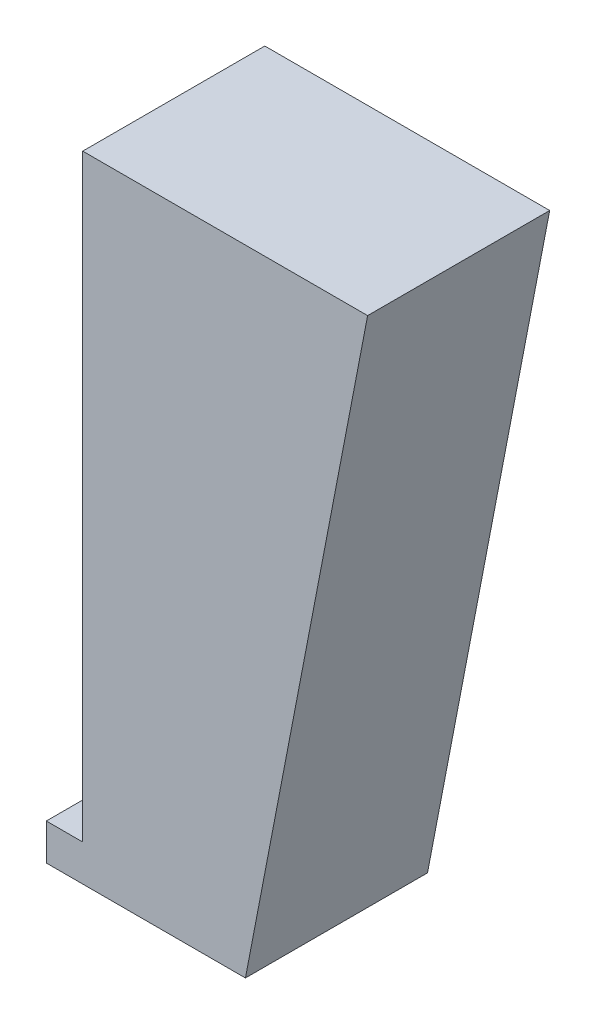
SolidWorks part; units mm, degrees
ref_plane "Front Plane" through (0, 0, 0) normal (0, 0, 1) x (1, 0, 0)
ref_plane "Top Plane" through (0, 0, 0) normal (0, 1, 0) x (1, 0, 0)
ref_plane "Right Plane" through (0, 0, 0) normal (1, 0, 0) x (0, 0, -1)
sketch "Sketch1" plane through (0, 0, 0) normal (0, 0, 1) x (1, 0, 0)
  line L0 (-6.0222, 12.5) -> (0.9778, 12.5)
  line L3 (55.7438, 127.5222) -> (32.2556, 5.5)
  line L4 (32.2556, 5.5) -> (-6.0222, 5.5)
  line L5 (-6.0222, 5.5) -> (-6.0222, 12.5)
  line L7 (0.9778, 12.5) -> (0.9778, 127.5222)
  line L10 (0.9778, 127.5222) -> (55.7438, 127.5222)
  dimension "D1" = 54.766
  dimension "D2" = 115.0222
  dimension "D3" = 122.0222
  dimension "D4" = 38.2777
  dimension "D5" = 7
extrude "Boss-Extrude1" add sketch "Sketch1" along normal blind 35
